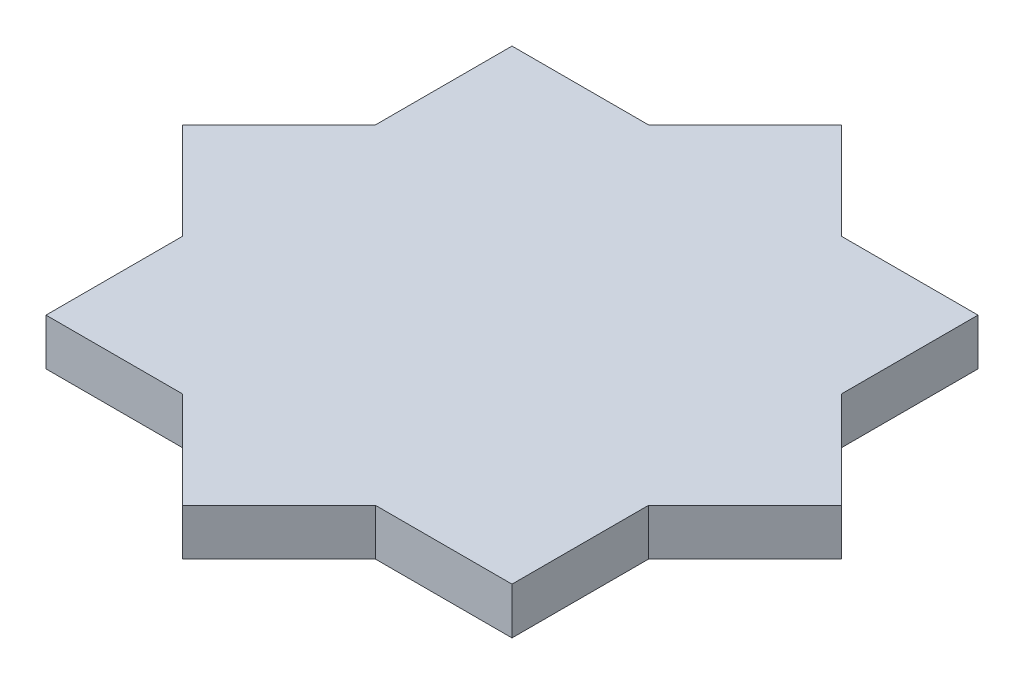
SolidWorks part; units mm, degrees
ref_plane "前视基准面" through (0, 0, 0) normal (0, 0, 1) x (1, 0, 0)
ref_plane "上视基准面" through (0, 0, 0) normal (0, 1, 0) x (1, 0, 0)
ref_plane "右视基准面" through (0, 0, 0) normal (1, 0, 0) x (0, 0, -1)
other "Configuration Table"
sketch "草图1" plane through (0, 0, 0) normal (0, 1, 0) x (1, 0, 0)
  line L0 (-21.2132, 0) -> (0, -21.2132)
  line L1 (-15, -15) -> (15, -15) construction
  line L2 (-15, -15) -> (-15, 15) construction
  line L3 (-15, 15) -> (15, 15) construction
  line L4 (15, -15) -> (15, 15) construction
  line L5 (-15, -15) -> (15, 15) construction
  line L6 (-15, 15) -> (15, -15) construction
  line L7 (-21.2132, 0) -> (0, 21.2132)
  line L8 (0, 21.2132) -> (21.2132, 0)
  line L9 (0, -21.2132) -> (21.2132, 0)
  line L10 (-21.2132, 0) -> (21.2132, 0) construction
  line L11 (0, 21.2132) -> (0, -21.2132) construction
  circle A0 centre (0, 0) radius 2.5 construction
  point P0 (0, 0)
  point P5 (0, 0)
  dimension "D2" = 5
  dimension "D1" = 30
extrude "凸台-拉伸1" add sketch "草图1" along normal blind 3
sketch "草图2" plane through (0, 0, 0) normal (0, 1, 0) x (1, 0, 0)
  line L1 (-15, 15) -> (15, 15)
  line L2 (-15, 15) -> (-15, -15)
  line L3 (-15, -15) -> (15, -15)
  line L4 (15, 15) -> (15, -15)
extrude "凸台-拉伸2" add sketch "草图2" along normal blind 3
sketch "草图3" plane through (0, 0, 0) normal (0, -1, 0) x (-1, 0, 0)
  line L0 (-6.2132, 15) -> (6.2132, 15) construction
  line L1 (0, 21.2132) -> (0, 15) construction
  line L2 (-6.2132, 15) -> (-15, 6.2132) construction
  line L3 (-15, 15) -> (-10.6066, 10.6066) construction
  line L4 (-15, 6.2132) -> (-15, -6.2132) construction
  line L5 (-15, -6.2132) -> (-6.2132, -15) construction
  line L6 (-6.2132, -15) -> (6.2132, -15) construction
  line L7 (6.2132, -15) -> (15, -6.2132) construction
  line L8 (15, -6.2132) -> (15, 6.2132) construction
  line L9 (15, 6.2132) -> (6.2132, 15) construction
  line L10 (-15, 6.2132) -> (0, 0) construction
  line L11 (0, 0) -> (-6.2132, 15) construction
  line L12 (-6.2132, 15) -> (-7.5, 3.1066) construction
  line L13 (-15, 6.2132) -> (-3.1066, 7.5) construction
  line L14 (0, 0) -> (-10.6066, 10.6066) construction
  circle A0 centre (0, 0) radius 18.1066
  point P10 (0, 18.1066)
  point P16 (-7.0711, 7.0711)
  dimension "D1" = 15
  dimension "D2" = 6.2132
sketch "重心质点" plane through (0, 0, 0) normal (0, -1, 0) x (-1, 0, 0)
  line L0 (0, 0) -> (-7.0711, 7.0711) construction
  line L1 (0, 0) -> (0, 10) construction
  line L2 (0, 0) -> (7.0711, 7.0711) construction
  line L3 (0, 0) -> (10, 0) construction
  line L4 (0, 0) -> (7.0711, -7.0711) construction
  line L5 (0, 0) -> (0, -10) construction
  line L6 (0, 0) -> (-7.0711, -7.0711) construction
  line L7 (0, 0) -> (-10, 0) construction
  line L8 (-7.0711, 7.0711) -> (0, 10) construction
  line L9 (0, 10) -> (7.0711, 7.0711) construction
  line L10 (7.0711, 7.0711) -> (10, 0) construction
  line L11 (10, 0) -> (7.0711, -7.0711) construction
  line L12 (7.0711, -7.0711) -> (0, -10) construction
  line L13 (0, -10) -> (-7.0711, -7.0711) construction
  line L14 (-7.0711, -7.0711) -> (-10, 0) construction
  line L15 (-10, 0) -> (-7.0711, 7.0711) construction
  line L16 (0, 18.1066) -> (0, 10) construction
  line L17 (12.8033, 12.8033) -> (7.0711, 7.0711) construction
  line L18 (18.1066, 0) -> (10, 0) construction
  line L19 (12.8033, -12.8033) -> (7.0711, -7.0711) construction
  line L20 (0, -18.1066) -> (0, -10) construction
  line L21 (-12.8033, -12.8033) -> (-7.0711, -7.0711) construction
  line L22 (-18.1066, 0) -> (-10, 0) construction
  line L23 (-12.8033, 12.8033) -> (-7.0711, 7.0711) construction
  line L24 (-15, 15) -> (-10.6066, 10.6066) construction
  line L25 (-12.8033, 12.8033) -> (-18.1066, 0) construction
  line L26 (-18.1066, 0) -> (-12.8033, -12.8033) construction
  line L27 (-12.8033, -12.8033) -> (0, -18.1066) construction
  line L28 (0, -18.1066) -> (12.8033, -12.8033) construction
  line L29 (12.8033, -12.8033) -> (18.1066, 0) construction
  line L30 (18.1066, 0) -> (12.8033, 12.8033) construction
  line L31 (12.8033, 12.8033) -> (0, 18.1066) construction
  line L32 (0, 18.1066) -> (-12.8033, 12.8033) construction
  point P5 (0, 12.372)
  point P13 (0, 0)
  point P30 (0, 0)
  dimension "D3" = 10
  dimension "D4" = 18.1066
  dimension "D5" = 7.6537
  dimension "D6" = 13.8582
  dimension "D7" = 5.7346
  dimension "D8" = 12.372
  dimension "D1" = 8
  dimension "D2" = 8
equation "\"D7@重心质点\"=8.11*0.7071"
